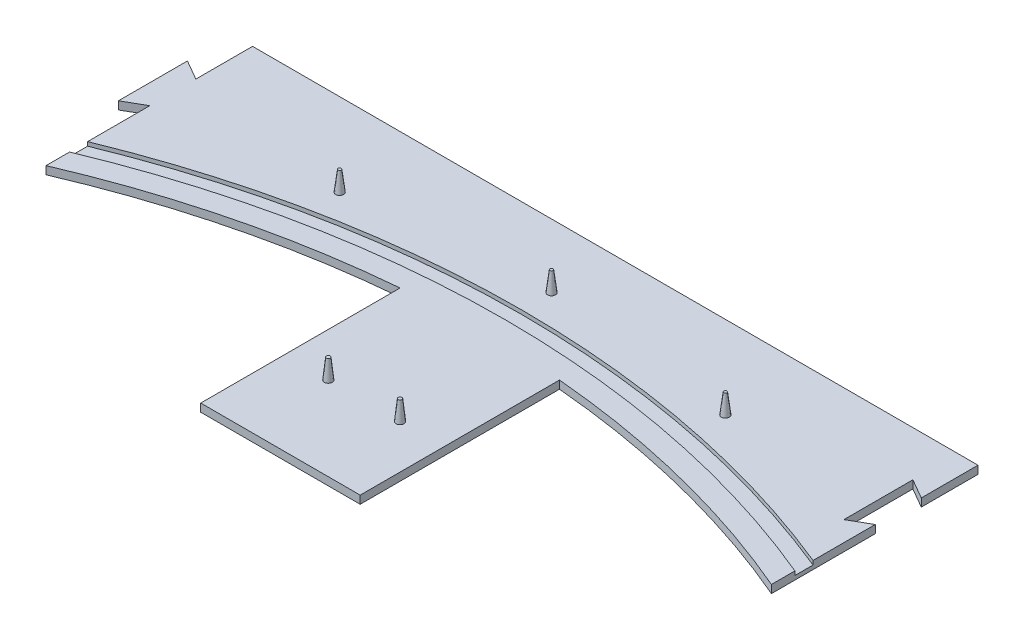
SolidWorks part; units mm, degrees
ref_plane "Front Plane" through (0, 0, 0) normal (0, 0, 1) x (1, 0, 0)
ref_plane "Top Plane" through (0, 0, 0) normal (0, 1, 0) x (1, 0, 0)
ref_plane "Right Plane" through (0, 0, 0) normal (1, 0, 0) x (0, 0, -1)
sketch "Sketch1" plane through (0, 0, 0) normal (0, 1, 0) x (1, 0, 0)
  line L7 (264, 0) -> (264, 131.98)
  line L9 (131.9796, 264) -> (0, 264)
  line L14 (131.9796, 264) -> (264, 131.98)
  line L15 (0, 264) -> (0, 0) construction
  line L16 (264, 109.3524) -> (186.6762, 186.6762) [skipped]
  line L17 (0, 0) -> (264, 0) construction
  line L18 (264, -131.9796) -> (131.98, -264)
  line L19 (-264, 0) -> (-264, -109.3524) [skipped]
  line L20 (-186.6762, 186.6762) -> (-264, 109.3524) [skipped]
  line L21 (-186.6762, -186.6762) -> (-109.3524, -264) [skipped]
  line L22 (0, -264) -> (109.3524, -264) [skipped]
  line L23 (186.6762, -186.6762) -> (264, -109.3524) [skipped]
  line L24 (264, -131.9796) -> (264, 0)
  line L25 (0, -264) -> (131.98, -264)
  line L26 (-131.9796, -264) -> (-264, -131.98)
  line L27 (-131.9796, -264) -> (0, -264)
  line L28 (-264, 0) -> (-264, -131.98)
  line L29 (-264, 131.9796) -> (-131.98, 264)
  line L30 (-264, 131.9796) -> (-264, 0)
  line L31 (0, 264) -> (-131.98, 264)
  arc A0 (264, 0) -> (0, 264) centre (0, 0) ccw construction
  point P33 (0, 0)
  dimension "D1" = 264
  dimension "D2" = 280
  dimension "D3" = 131.98
  dimension "D4" = 4
extrude "baseplate profile" add sketch "Sketch1" against normal blind 2
sketch "Sketch2" plane through (0, 0, 0) normal (0, 1, 0) x (1, 0, 0)
  line L0 (0, -248) -> (0, 248) construction
  circle A0 centre (0, 248) radius 1
  dimension "D2" = 2
  dimension "D1" = 496
extrude "M3 pins" add sketch "Sketch2" along normal blind 5 draft 7
sketch "center line" plane through (0, 0, 0) normal (0, 0, 1) x (1, 0, 0)
  line L0 (0, 0) -> (0, 200) construction
  dimension "D1" = 200
pattern_circular "CirPattern1" count 32 over 360 about axis through (0, 0, 0) along (0, 1, 0) of "M3 pins"
sketch "Sketch4" plane through (0, 0, 0) normal (0, 1, 0) x (1, 0, 0)
  line L0 (0, 0) -> (0, 201) construction
  line L1 (-9, 201) -> (9, 201) construction
  circle A0 centre (9, 201) radius 1
  circle A1 centre (-9, 201) radius 1
  point P5 (0, 201)
  dimension "D3" = 2
  dimension "D4" = 2
  dimension "D1" = 201
  dimension "D2" = 18
extrude "pillar pins" add sketch "Sketch4" along normal blind 5 draft 6
pattern_circular "CirPattern2" count 6 over 360 about axis through (0, 0, 0) along (0, 1, 0) of "pillar pins"
sketch "Sketch5" plane through (0, 0, 0) normal (0, 1, 0) x (1, 0, 0)
  line L0 (-193.0402, 193.0402) -> (193.0402, -193.0402) construction
  line L1 (-131.9796, -264) -> (131.98, -264) construction
  circle A0 centre (-193.0402, 193.0402) radius 3
  dimension "D3" = 6
  dimension "D1" = 546
  dimension "D2" = 45
extrude "M8 hole -1" add sketch "Sketch5" along normal blind 5 draft 12
pattern_circular "M8 -1 pattern" count 4 over 360 about axis through (0, 0, 0) along (0, 1, 0) of "M8 hole -1"
sketch "Sketch6" plane through (0, 0, 0) normal (0, 1, 0) x (1, 0, 0)
  line L0 (0, 0) -> (0, -324.5462) construction
  line L1 (0, 0) -> (-438.1399, 0) construction
  circle A0 centre (-125, -250) radius 3
  dimension "D1" = 6
  dimension "D2" = 125
  dimension "D3" = 250
extrude "M8 -2" add sketch "Sketch6" along normal blind 5 draft 12
pattern_circular "M8 -2 pattern" count 4 over 360 about axis through (0, 0, 0) along (0, 1, 0) of "M8 -2"
pattern_circular "M8 -3" count 2 over 36.9 about axis through (0, 0, 0) along (0, 1, 0) of "M8 -2 pattern", "M8 -2"
sketch "Sketch7" [suppressed] plane through (0, 0, 0) normal (0, 1, 0) x (1, 0, 0)
  line L1 (94.9211, 86.9806) -> (274.9211, 86.9806)
  line L2 (94.9211, 86.9806) -> (94.9211, -93.0194)
  line L3 (94.9211, -93.0194) -> (274.9211, -93.0194)
  line L4 (274.9211, 86.9806) -> (274.9211, -93.0194)
  dimension "D1" = 180
  dimension "D2" = 180
sketch "Sketch8" plane through (0, 0, 0) normal (0, 1, 0) x (1, 0, 0)
  line L0 (0, 0) -> (0, -180) construction
  line L1 (20, -230) -> (-20, -230)
  line L2 (20, -230) -> (20, -180)
  line L3 (20, -180) -> (-20, -180)
  line L4 (-20, -230) -> (-20, -180)
  line L5 (0, 0) -> (115.434, -199.9375)
  line L6 (0, 0) -> (-115.434, -199.9375)
  arc A0 (20, -230) -> (115.434, -199.9375) centre (0, 0) ccw
  arc A1 (-20, -230) -> (-115.434, -199.9375) centre (0, 0) cw
  point P7 (0, -180)
  dimension "D4" = 30
  dimension "D1" = 40
  dimension "D2" = 180
  dimension "D3" = 50
extrude "cut center" cut sketch "Sketch8" against normal through all contours L5 L0 L3 L2 A0 | L0 L6 A1 L4 L3
pattern_circular "CirPattern7" count 6 over 360 about axis through (0, 0, 0) along (0, 1, 0) of "cut center"
sketch "middle piece space " plane through (0, 0, 0) normal (0, 1, 0) x (1, 0, 0)
  line L0 (0, 0) -> (-200, 0) construction
  line L1 (91, 110) -> (-91, 110)
  line L2 (-110, 91) -> (-290, 91)
  line L3 (-110, 91) -> (-110, -91)
  line L4 (-110, -91) -> (-290, -91)
  line L5 (-290, 91) -> (-290, -91)
  line L6 (-110, 91) -> (-290, -91) construction
  line L7 (-110, -91) -> (-290, 91) construction
  line L8 (91, 110) -> (91, 290)
  line L9 (91, 290) -> (-91, 290)
  line L10 (-91, 110) -> (-91, 290)
  line L11 (110, -91) -> (110, 91)
  line L12 (110, -91) -> (290, -91)
  line L13 (290, -91) -> (290, 91)
  line L14 (110, 91) -> (290, 91)
  line L15 (-91, -110) -> (91, -110)
  line L16 (-91, -110) -> (-91, -290)
  line L17 (-91, -290) -> (91, -290)
  line L18 (91, -110) -> (91, -290)
  point P22 (0, 0)
  dimension "D1" = 182
  dimension "D2" = 200
  dimension "D3" = 180
  dimension "D4" = 4
sketch "Sketch11" [suppressed] plane through (0, 0, 0) normal (0, 1, 0) x (1, 0, 0)
  line L0 (-131.9796, -264) -> (131.98, -264) construction
  line L1 (-87.5, -87.5) -> (-264, -87.5)
  line L2 (-87.5, -87.5) -> (-87.5, -264)
  line L3 (-87.5, -264) -> (-264, -264)
  line L4 (-264, -87.5) -> (-264, -264)
  line L5 (-264, 131.9796) -> (-264, -131.98) construction
  line L6 (-110, -87.5) -> (-290, -87.5) construction
  line L7 (-87.5, -110) -> (-87.5, -290) construction
sketch "Sketch12" [suppressed] plane through (0, -2, 0) normal (0, -1, 0) x (1, 0, 0)
  line L0 (-110, 87.5) -> (-290, 87.5) construction
  line L1 (303.8847, 330.4144) -> (-306.2965, 330.4144)
  line L2 (303.8847, 330.4144) -> (303.8847, -333.6301)
  line L3 (303.8847, -333.6301) -> (-306.2965, -333.6301)
  line L4 (-306.2965, 330.4144) -> (-306.2965, -333.6301)
  line L5 (-200, 87.5) -> (-290, 87.5)
  line L6 (-200, 87.5) -> (-200, -87.5)
  line L7 (-200, -87.5) -> (-290, -87.5)
  line L8 (-290, 87.5) -> (-290, -87.5)
extrude "Cut-Extrude1" [suppressed] cut sketch "Sketch12" against normal blind 10
sketch "Sketch13" [suppressed] plane through (0, 0, 0) normal (0, 1, 0) x (1, 0, 0)
  line L0 (-110, -87.5) -> (-290, -87.5) construction
  line L1 (-256.9904, -95) -> (-231.0096, -95)
  line L2 (-231.0096, -95) -> (-244, -72.5)
  line L3 (-244, -72.5) -> (-256.9904, -95)
  line L4 (-264, 131.9796) -> (-264, -131.98) construction
  circle A0 centre (-244, -87.5) radius 7.5 construction
  dimension "D1" = 15
  dimension "D2" = 20
extrude "Boss-Extrude1" [suppressed] add sketch "Sketch13" against normal up to surface (2 mm away)
sketch "Sketch14" [suppressed] plane through (0, 0, 0) normal (0, 1, 0) x (1, 0, 0)
  line L0 (-110, 87.5) -> (-290, 87.5) construction
  line L1 (-256.9904, 80) -> (-231.0096, 80)
  line L2 (-231.0096, 80) -> (-244, 102.5)
  line L3 (-244, 102.5) -> (-256.9904, 80)
  line L4 (-264, 131.9796) -> (-264, -131.98) construction
  circle A0 centre (-244, 87.5) radius 7.5 construction
  dimension "D1" = 15
  dimension "D2" = 20
extrude "Cut-Extrude2" [suppressed] cut sketch "Sketch14" against normal up to surface (2 mm away) contours L2 L3 L1
sketch "Sketch15" plane through (0, -2, 0) normal (0, -1, 0) x (-1, 0, 0)
  line L0 (91, 110) -> (91, 290) construction
  line L1 (-351.7406, 319.4147) -> (442.5007, 319.4147)
  line L2 (-351.7406, 319.4147) -> (-351.7406, -437.747)
  line L3 (-351.7406, -437.747) -> (442.5007, -437.747)
  line L4 (442.5007, 319.4147) -> (442.5007, -437.747)
  line L5 (-91, 290) -> (91, 290)
  line L6 (-91, 290) -> (-91, 110)
  line L7 (-91, 110) -> (91, 110)
  line L8 (91, 290) -> (91, 110)
  line L10 (-91, 290) -> (91, 290) construction
  line L12 (-91, 110) -> (-91, 290) construction
  line L13 (-91, 110) -> (91, 110) construction
extrude "Cut-Extrude3" cut sketch "Sketch15" against normal through all
sketch "Sketch16" plane through (0, 0, 0) normal (0, 1, 0) x (1, 0, 0)
  line L0 (-91, 110) -> (-91, 290) construction
  line L1 (-96, 252.6603) -> (-96, 235.3397)
  line L2 (-96, 235.3397) -> (-81, 244)
  line L3 (-81, 244) -> (-96, 252.6603)
  line L4 (91, 264) -> (-91, 264) construction
  circle A0 centre (-91, 244) radius 5 construction
  dimension "D2" = 10
  dimension "D1" = 20
extrude "Boss-Extrude2" add sketch "Sketch16" against normal up to surface (2 mm away) up to face at (0, -2, -222.2522)
sketch "Sketch17" plane through (0, 0, 0) normal (0, 1, 0) x (1, 0, 0)
  line L0 (91, 110) -> (91, 290) construction
  line L1 (101, 244) -> (86, 252.6603)
  line L2 (86, 252.6603) -> (86, 235.3397)
  line L3 (86, 235.3397) -> (101, 244)
  line L4 (91, 264) -> (-91, 264) construction
  circle A0 centre (91, 244) radius 5 construction
  dimension "D2" = 10
  dimension "D1" = 20
extrude "Cut-Extrude4" cut sketch "Sketch17" against normal through all
sketch "Sketch18" plane through (0, 0, 0) normal (0, 1, 0) x (1, 0, 0)
  circle A0 centre (0, 0) radius 236.3
  circle A1 centre (0, 0) radius 240.5
  dimension "D1" = 472.6
  dimension "D2" = 481
extrude "Cut-Extrude5" cut sketch "Sketch18" against normal blind 1
